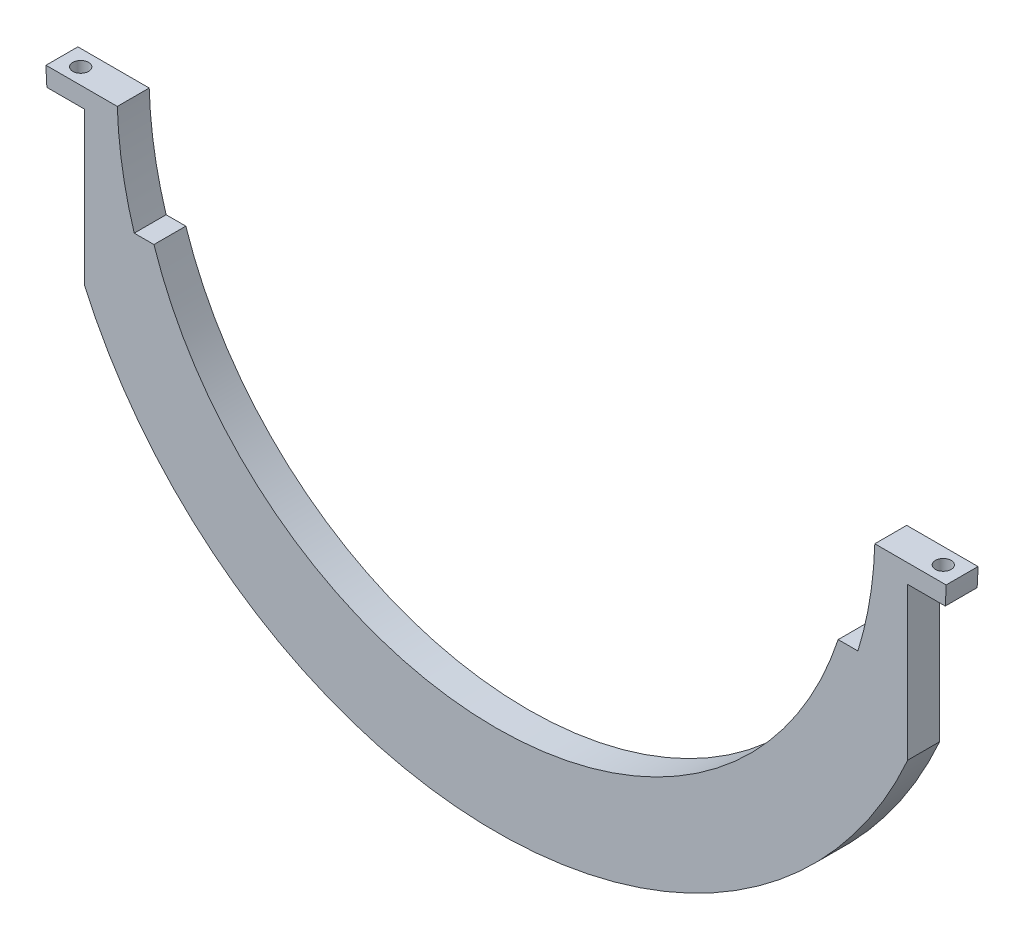
SolidWorks part; units mm, degrees
ref_plane "前视基准面" through (0, 0, 0) normal (0, 0, 1) x (1, 0, 0)
ref_plane "上视基准面" through (0, 0, 0) normal (0, 1, 0) x (1, 0, 0)
ref_plane "右视基准面" through (0, 0, 0) normal (1, 0, 0) x (0, 0, -1)
sketch "草图1" plane through (0, 0, 0) normal (0, 0, 1) x (1, 0, 0)
  line L2 (-119.733, -8) -> (-109.733, -8)
  line L3 (-109.733, -8) -> (-109.733, -48.566)
  line L4 (-96.4417, -30) -> (-91.1921, -30)
  line L5 (0, 0) -> (0, -94.1683) construction
  line L6 (119.733, -8) -> (109.733, -8)
  line L7 (91.1921, -30) -> (96.4417, -30)
  line L8 (109.733, -8) -> (109.733, -48.566)
  line L9 (-140.658, -3) -> (154.088, -3) construction
  line L10 (-119.9625, -3) -> (-100.9554, -3)
  line L11 (100.9554, -3) -> (119.9625, -3)
  arc A0 (-119.9625, -3) -> (-119.733, -8) centre (0, 0) ccw
  arc A1 (-91.1921, -30) -> (91.1921, -30) centre (0, 0) ccw
  arc A2 (-109.733, -48.566) -> (109.733, -48.566) centre (0, 0) ccw
  arc A3 (119.733, -8) -> (119.9625, -3) centre (0, 0) ccw
  arc A4 (-100.9554, -3) -> (-96.4417, -30) centre (0, 0) ccw
  arc A5 (96.4417, -30) -> (100.9554, -3) centre (0, 0) ccw
  dimension "D1" = 96
  dimension "D2" = 120
  dimension "D4" = 101
  dimension "D3" = 10
  dimension "D5" = 30
  dimension "D6" = 5
  dimension "D7" = 3
extrude "凸台-拉伸1" add sketch "草图1" along normal blind 8.5
sketch "草图2" plane through (0, -3, 0) normal (0, 1, 0) x (1, 0, 0)
  line L0 (119.9625, -8.5) -> (119.9625, 0) construction
  line L1 (-119.9625, -8.5) -> (-119.9625, 0) construction
  line L2 (-100.9554, -8.5) -> (-119.9625, -8.5) construction
  line L3 (119.9625, -8.5) -> (100.9554, -8.5) construction
  circle A0 centre (-114.9625, -4.25) radius 2.1
  circle A1 centre (114.9625, -4.25) radius 2.1
  dimension "D1" = 4.2
  dimension "D2" = 4.2
  dimension "D3" = 5
  dimension "D4" = 5
  dimension "D5" = 4.25
  dimension "D6" = 4.25
extrude "切除-拉伸1" cut sketch "草图2" against normal blind 10
